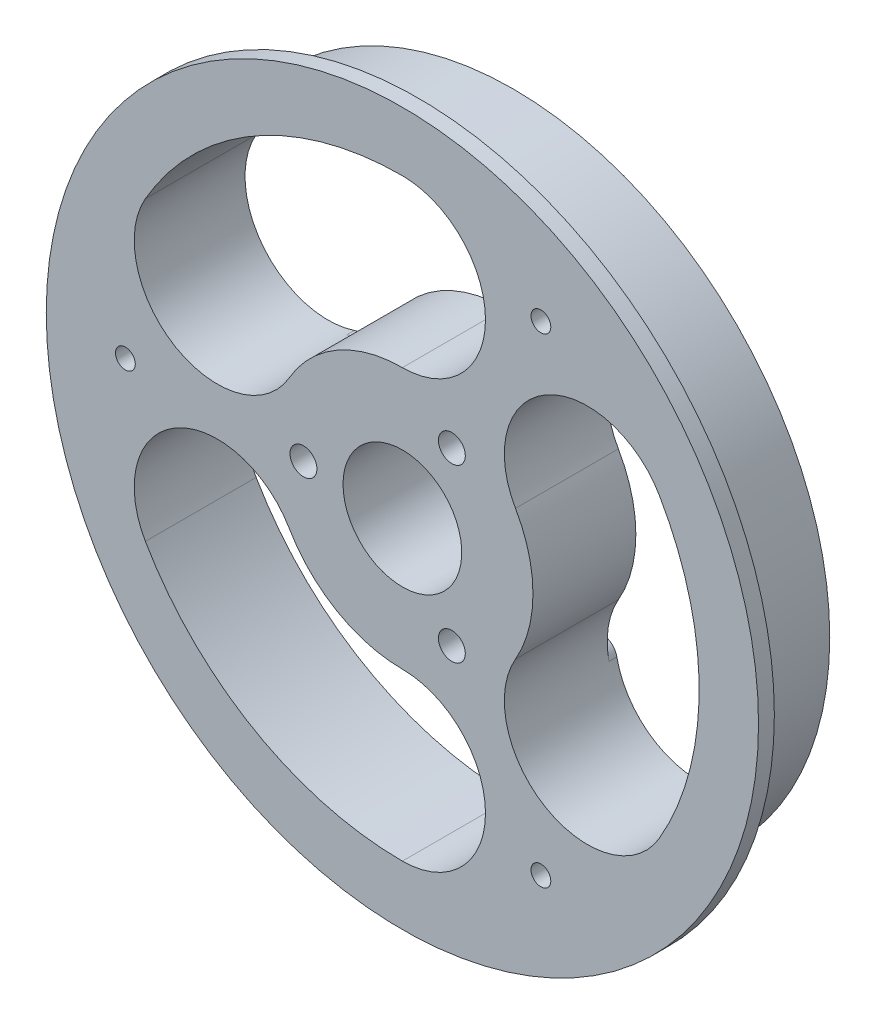
SolidWorks part; units mm, degrees
material "Сплав 2024"
ref_plane "Спереди" through (0, 0, 0) normal (0, 0, 1) x (1, 0, 0)
ref_plane "Сверху" through (0, 0, 0) normal (0, 1, 0) x (1, 0, 0)
ref_plane "Справа" through (0, 0, 0) normal (1, 0, 0) x (0, 0, -1)
sketch "Эскиз1" plane through (0, 0, 0) normal (0, 0, 1) x (1, 0, 0)
  circle A0 centre (0, 0) radius 40
  dimension "D1" = 80
extrude "Бобышка-Вытянуть1" add sketch "Эскиз1" along normal blind 12
sketch "Эскиз8" plane through (0, 0, 12) normal (0, 0, 1) x (1, 0, 0)
  circle A0 centre (0, 0) radius 45
  dimension "D1" = 90
extrude "Бобышка-Вытянуть3" add sketch "Эскиз8" along normal blind 2
sketch "Эскиз2" plane through (0, 0, 14) normal (0, 0, -1) x (-1, 0, 0)
  circle A0 centre (0, 0) radius 7.5
  dimension "D1" = 15
extrude "Вырез-Вытянуть1" cut sketch "Эскиз2" along normal through all
hole_wizard "Отверстие с зазором M31" positions "Эскиз4" profile "Эскиз3" hole size "M3" standard "Ansi Metric"
sketch "Эскиз4" plane through (-6.6635, -3.8899, 14) normal (0, 0, -1) x (-1, 0, 0)
  point P0 (20.5996, 37.0106)
sketch "Эскиз3" plane through (-27.2631, 33.1208, 14) normal (1, 0, 0) x (0, -1, 0)
  line L0 (0, 0) -> (0, 14)
  line L1 (0, 14) -> (1.7, 14)
  line L2 (1.7, 14) -> (1.7, 0)
  line L5 (1.7, 0) -> (0, 0)
  line L11 (0, -6.35) -> (0, 107.95) construction
  dimension "Диаметр сквозного отверстия" = 3.4
  dimension "Глубина сквозного отверстия" = 14
sketch "Эскиз10" plane through (0, 0, 0) normal (0, 0, -1) x (-1, 0, 0)
  line L1 (0, 49.276) -> (0, -49.5343) construction
  line L2 (46.4311, 26.807) -> (-46.4311, -26.807) construction
  arc A2 (32.476, -18.75) -> (14.2894, -8.25) centre (23.3827, -13.5) ccw
  arc A3 (32.476, 18.75) -> (0, 37.5) centre (0, 0) ccw
  circle A4 centre (0, 0) radius 27 construction
  arc A5 (0, 37.5) -> (0, 16.5) centre (0, 27) ccw
  arc A6 (14.2894, 8.25) -> (32.476, 18.75) centre (23.3827, 13.5) ccw
  arc A7 (14.2894, 8.25) -> (0, 16.5) centre (0, 0) ccw
  arc A8 (0, -16.5) -> (14.2894, -8.25) centre (0, 0) ccw
  arc A9 (0, -16.5) -> (0, -37.5) centre (0, -27) ccw
  arc A10 (0, -37.5) -> (32.476, -18.75) centre (0, 0) ccw
  arc A11 (-32.476, -18.75) -> (-14.2894, -8.25) centre (-23.3827, -13.5) ccw
  arc A12 (-14.2894, 8.25) -> (-14.2894, -8.25) centre (0, 0) ccw
  arc A13 (-14.2894, 8.25) -> (-32.476, 18.75) centre (-23.3827, 13.5) ccw
  arc A14 (-32.476, 18.75) -> (-32.476, -18.75) centre (0, 0) ccw
  point P28 (0, 0)
  dimension "D1" = 3
  dimension "D2" = 75
  dimension "D3" = 54
  dimension "D4" = 60
sketch "Эскиз11" plane through (0, 0, 14) normal (0, 0, 1) x (1, 0, 0)
  line L1 (6.25, 10.8253) -> (-6.25, -10.8253) construction
  line L2 (12.5, 0) -> (-12.5, 0) construction
  line L3 (-6.25, 10.8253) -> (6.25, -10.8253) construction
  circle A0 centre (0, 0) radius 12.5 construction
  dimension "D1" = 25
  dimension "D2" = 60
  dimension "D3" = 60
hole_wizard "Отверстие с зазором M32" positions "Эскиз13" profile "Эскиз12" hole size "M3" standard "Ansi Metric" end condition through all
sketch "Эскиз13" plane through (0, 0, 14) normal (0, 0, 1) x (1, 0, 0)
  point P0 (6.25, 10.8253)
  point P3 (-12.5, 0)
  point P9 (6.25, -10.8253)
sketch "Эскиз12" plane through (6.25, 10.8253, 14) normal (1, 0, 0) x (0, -1, 0)
  line L0 (0, 0) -> (0, 14)
  line L1 (0, 14) -> (1.7, 14)
  line L2 (1.7, 14) -> (1.7, 0)
  line L5 (1.7, 0) -> (0, 0)
  line L11 (0, -6.35) -> (0, 107.95) construction
  dimension "Диаметр сквозного отверстия" = 3.4
  dimension "Глубина сквозного отверстия" = 14
extrude "Вырез-Вытянуть2" cut sketch "Эскиз10" against normal through all
sketch "Эскиз14" plane through (0, 0, 0) normal (0, 0, -1) x (-1, 0, 0)
  line L2 (-55.8661, 0) -> (55.9948, 0) construction
  line L3 (-20, 34.641) -> (20, -34.641) construction
  line L4 (20, 34.641) -> (-20, -34.641) construction
  circle A0 centre (0, 0) radius 40 construction
  circle A1 centre (0, 0) radius 40 construction
  circle A2 centre (0, 0) radius 35 construction
  dimension "D3" = 70
  dimension "D1" = 60
  dimension "D2" = 60
hole_wizard "Отверстие обработанное метчиком M3x0.51" positions "Эскиз16" profile "Эскиз15" tap size "M3x0.5" standard "Ansi Metric" end condition through all
sketch "Эскиз16" plane through (0, 0, 0) normal (0, 0, -1) x (-1, 0, 0)
  line L0 (-20, 34.641) -> (20, -34.641) construction
  line L1 (20, 34.641) -> (-20, -34.641) construction
  line L2 (-55.8661, 0) -> (55.9948, 0) construction
  circle A0 centre (0, 0) radius 35 construction
  point P0 (-17.5, 30.3109)
  point P6 (35, 0)
  point P12 (-17.5, -30.3109)
sketch "Эскиз15" plane through (17.5, 30.3109, 0) normal (1, 0, 0) x (0, 1, 0)
  line L0 (0, 0) -> (0, 14)
  line L1 (0, 14) -> (1.25, 14)
  line L2 (1.25, 14) -> (1.25, 0)
  line L5 (1.25, 0) -> (0, 0)
  line L11 (0, -6.35) -> (0, 107.95) construction
  dimension "Диаметр проходного сверла" = 2.5
  dimension "Глубина проходного сверла" = 14
cosmetic thread "Отверстие резьбы4" parameters "D2"=3
cosmetic thread "Отверстие резьбы5" parameters "D2"=3
cosmetic thread "Отверстие резьбы6" parameters "D2"=3
sketch "Эскиз18" plane through (0, 0, 0) normal (0, 0, -1) x (-1, 0, 0)
  circle A0 centre (0, 0) radius 17.5
  dimension "D1" = 35
extrude "Вырез-Вытянуть4" cut sketch "Эскиз18" against normal blind 1
fillet "Скругление1" radius 2 6 edges at (-16.6253, 5.4633, 0.5) (-16.6253, -5.4633, 0.5) (3.5813, -17.1296, 0.5) (13.044, -11.6663, 0.5) (3.5813, 17.1296, 0.5) (13.044, 11.6663, 0.5)
sketch "Эскиз19" plane through (0, 0, 0) normal (0, 0, 1) x (1, 0, 0)
  line L0 (45, -26.2905) -> (45, -45) construction
  line L1 (45, -45) -> (32.5364, -45) construction
  circle A0 centre (0, 0) radius 45 construction
